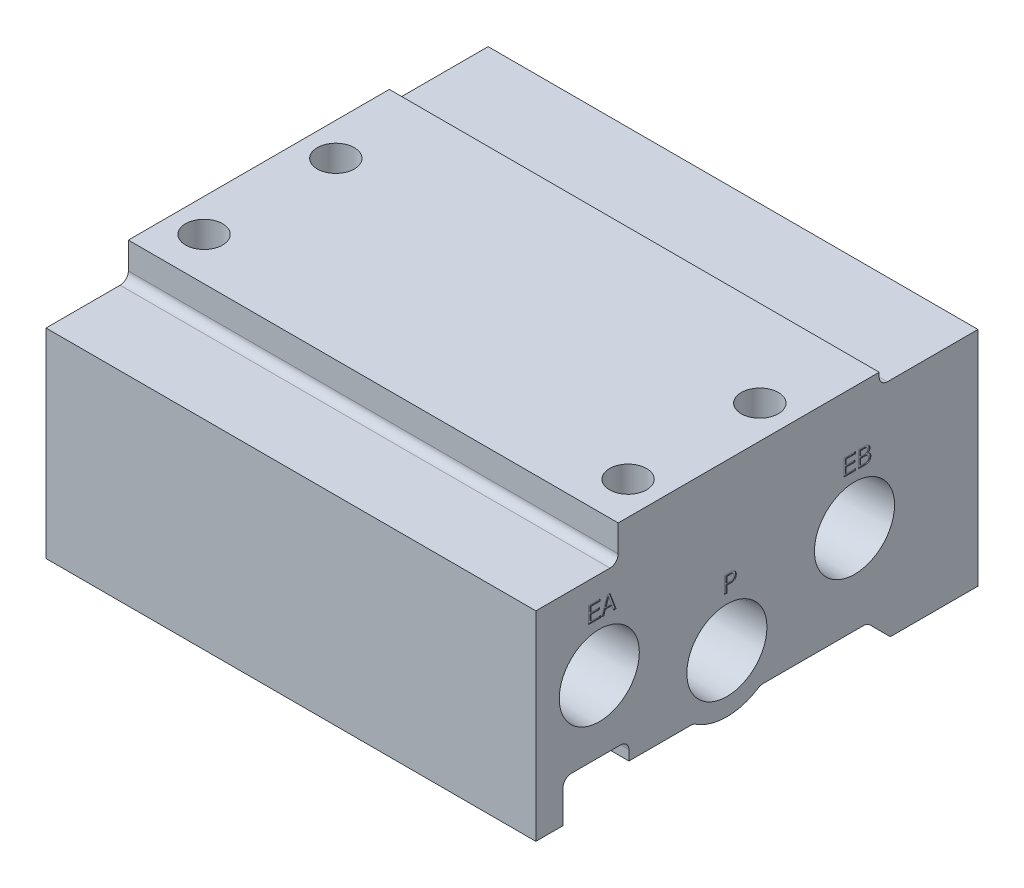
SolidWorks part; units mm, degrees
material "6061-T6 (SS)"
ref_plane "Front" through (0, 0, 0) normal (0, 0, 1) x (1, 0, 0)
ref_plane "Top" through (0, 0, 0) normal (0, 1, 0) x (1, 0, 0)
ref_plane "Right" through (0, 0, 0) normal (1, 0, 0) x (0, 0, -1)
sketch "Alum Ext Sketch" plane through (0, 0, 0) normal (1, 0, 0) x (0, 0, -1)
  line L1 (-26.85, 0) -> (26.85, 0)
  line L2 (-26.85, 0) -> (-26.85, -28.5)
  line L4 (26.85, 0) -> (26.85, -28.5)
  line L7 (0, 5.7104) -> (0, -31.2342) construction
  line L8 (-26.85, -28.5) -> (26.85, -28.5)
  dimension "Depth" = 53.7
  dimension "Height" = 28.5
extrude "Alum Ext" add sketch "Alum Ext Sketch" against normal up to surface (59.5 mm away)
sketch "Bottom_Profile 20 Sketch" [suppressed] plane through (0, 0, 0) normal (1, 0, 0) x (0, 0, -1)
  line L0 (-1, 0) -> (-1, -38.4475) construction
  line L1 (-21.54, -20) -> (-21.54, -13.45)
  line L2 (-24.5, -20) -> (24.5, -20) construction
  line L3 (-21.54, -13.45) -> (-21.1875, -13.45)
  line L4 (-13.8125, -13.45) -> (-4.6875, -13.45)
  line L5 (11.8125, -13.45) -> (2.6875, -13.45)
  line L6 (21.54, -13.45) -> (19.1875, -13.45)
  line L7 (21.54, -20) -> (21.54, -13.45)
  line L8 (24.5, -20) -> (24.5, 0) construction
  line L9 (-24.5, 0) -> (-24.5, -20) construction
  line L10 (24.5, 0) -> (-24.5, 0) construction
  line L11 (21.54, -16.725) -> (24.5, -16.725) construction
  line L12 (-21.54, -16.725) -> (-24.5, -16.725) construction
  line L13 (-24.5, -20) -> (-24.5, 0) construction
  line L14 (-21.54, -20) -> (21.54, -20)
  line L15 (-10.2716, -5) -> (-8.2284, -5)
  line L17 (-10.9481, -11.65) -> (-7.5519, -11.65)
  line L18 (-1, 9.9528) -> (-1, -11.3216) construction
  line L19 (8.9481, -11.65) -> (5.5519, -11.65)
  line L20 (8.2716, -5) -> (6.2284, -5)
  line L21 (24.5, 0) -> (-24.5, 0) construction
  arc A0 (-21.1875, -13.45) -> (-13.8125, -13.45) centre (-17.5, -7.5) ccw
  arc A1 (-4.6875, -13.45) -> (2.6875, -13.45) centre (-1, -7.5) ccw
  arc A2 (19.1875, -13.45) -> (11.8125, -13.45) centre (15.5, -7.5) cw
  arc A3 (-10.7535, -5.6333) -> (-11.3849, -10.9067) centre (-17.5, -7.5) cw
  arc A4 (-10.7535, -5.6333) -> (-10.2716, -5) centre (-10.2716, -5.5) cw
  arc A5 (-10.9481, -11.65) -> (-11.3849, -10.9067) centre (-10.9481, -11.15) cw
  arc A6 (-7.5519, -11.65) -> (-7.1151, -10.9067) centre (-7.5519, -11.15) ccw
  arc A7 (-7.7465, -5.6333) -> (-8.2284, -5) centre (-8.2284, -5.5) ccw
  arc A8 (-7.7465, -5.6333) -> (-7.1151, -10.9067) centre (-1, -7.5) ccw
  arc A9 (5.7465, -5.6333) -> (5.1151, -10.9067) centre (-1, -7.5) cw
  arc A10 (5.7465, -5.6333) -> (6.2284, -5) centre (6.2284, -5.5) cw
  arc A11 (5.5519, -11.65) -> (5.1151, -10.9067) centre (5.5519, -11.15) cw
  arc A12 (8.9481, -11.65) -> (9.3849, -10.9067) centre (8.9481, -11.15) ccw
  arc A13 (8.7535, -5.6333) -> (8.2716, -5) centre (8.2716, -5.5) ccw
  arc A14 (8.7535, -5.6333) -> (9.3849, -10.9067) centre (15.5, -7.5) ccw
  dimension "D1" = 23.5
  dimension "Wall_Radius" = 7
  dimension "D2" = 0.5
  dimension "D4" = 5
  dimension "D3" = 1.8
  dimension "Thickness" = 2.96
  dimension "Port_Loc_Z" = 16.5
  dimension "Port_Loc_Y" = 12.5
  dimension "Body_Thickness" = 13.45
extrude "Bottom_Profile 20" [suppressed] cut sketch "Bottom_Profile 20 Sketch" against normal through all
fillet "Ext_Fillets" [suppressed] radius 0.25
sketch "MGT_Holes Sketch" plane through (0, 0, 0) normal (0, 1, 0) x (1, 0, 0)
  line L1 (-29.75, 26.85) -> (-29.75, -50.1534) construction
  line L2 (-59.5, 26.85) -> (0, 26.85) construction
  line L3 (0, 0) -> (0, 12.4211) construction
  line L4 (-59.5, -26.85) -> (0, -26.85) construction
  line L6 (-59.5, -26.85) -> (-59.5, 26.85) construction
  circle A0 centre (-55.5, 4.35) radius 2.25
  circle A1 centre (-55.5, -11.65) radius 2.25
  circle A4 centre (-4, 4.35) radius 2.25
  circle A5 centre (-4, -11.65) radius 2.25
  dimension "Dia" = 4.5
  dimension "Loc_X" = 4
  dimension "Loc_Z" = 15.2
  dimension "C_2_C" = 16
extrude "MGT_Holes" cut sketch "MGT_Holes Sketch" against normal through all
sketch "Top_Profile_41 Sketch" plane through (0, 0, 0) normal (1, 0, 0) x (0, 0, -1)
  line L0 (-26.85, -4.25) -> (-16.85, -4.25)
  line L1 (-16.85, -4.25) -> (-16.85, 0)
  line L2 (26.85, 0) -> (-26.85, 0) construction
  line L3 (14.85, 0) -> (14.85, -1.5)
  line L4 (14.85, -1.5) -> (26.85, -1.5)
  line L5 (26.85, -28.5) -> (26.85, 0) construction
  line L6 (-26.85, -28.5) -> (26.85, -28.5) construction
  line L7 (-26.85, 0) -> (-26.85, -28.5) construction
  line L8 (26.85, -1.5) -> (26.85, 0)
  line L9 (-26.85, 0) -> (-26.85, -4.25)
  line L10 (26.85, 0) -> (14.85, 0)
  line L11 (-16.85, 0) -> (-26.85, 0)
  dimension "Back" = 12
  dimension "Back Height" = 27
  dimension "Front" = 10
  dimension "Front_Height" = 24.25
extrude "Top_Profile_41" cut sketch "Top_Profile_41 Sketch" against normal through all
sketch "Bottom_Profile_41 Sketch" plane through (0, 0, 0) normal (1, 0, 0) x (0, 0, -1)
  line L0 (16.2, -28.5) -> (13.4, -25.7)
  line L1 (-26.85, -28.5) -> (26.85, -28.5) construction
  line L2 (13.4, -25.7) -> (0.4132, -25.7)
  line L3 (-15.55, -25.7) -> (-15.55, -23.5)
  line L4 (-15.55, -23.5) -> (-23.55, -23.5)
  line L5 (-23.55, -23.5) -> (-23.55, -28.5)
  line L6 (26.85, -28.5) -> (-26.85, -28.5) construction
  line L7 (26.85, -28.5) -> (26.85, -1.5) construction
  line L8 (-26.85, -4.25) -> (-26.85, -28.5) construction
  line L9 (-26.85, -28.5) -> (-26.85, -4.25) construction
  line L10 (-7.7132, -25.7) -> (-15.55, -25.7)
  line L11 (-23.55, -28.5) -> (16.2, -28.5)
  arc A0 (-7.7132, -25.7) -> (0.4132, -25.7) centre (-3.65, -20) ccw
  dimension "D1" = 8.5
  dimension "D2" = 23.2
  dimension "Radius" = 7
  dimension "Back_Width" = 13.45
  dimension "Back_Depth" = 2.8
  dimension "Front_Width" = 3.3
  dimension "Front_Depth" = 5
  dimension "Groove" = 8
  dimension "Angle" = 45
extrude "Bottom_Profile_41" cut sketch "Bottom_Profile_41 Sketch" against normal through all
fillet "Rounds_41" radius 1 7 edges at (-29.75, -4.25, 16.85) (-29.75, -1.5, -14.85) (-29.75, -25.7, -0.4132) (-29.75, -23.5, 23.55) (-29.75, -23.5, 15.55) (-29.75, -25.7, 7.7132) (-29.75, -25.7, -13.4)
sketch "Profile_42 Sketch" [suppressed] plane through (0, 0, 0) normal (1, 0, 0) x (0, 0, -1)
  line L0 (-13.9, -32) -> (-12.9, -31)
  line L1 (-27.85, -32) -> (27.85, -32) construction
  line L2 (-12.9, -31) -> (12.9, -31)
  line L3 (12.9, -31) -> (13.9, -32)
  line L4 (13.9, -32) -> (-13.9, -32)
  line L5 (0, 0) -> (0, -41.5568) construction
  dimension "Width" = 25.8
  dimension "Angle" = 90
  dimension "Depth" = 1
extrude "Profile_42" [suppressed] cut sketch "Profile_42 Sketch" against normal through all
fillet "Fillets_42" [suppressed] radius 0.5
sketch "20 Port Designations Sketch" [suppressed] plane through (2.9671, 0, 3.015) normal (0, 1, 0) x (0, 0, 1)
  line L0 (21.485, -51.4671) -> (-27.515, -51.4671) construction
  line L2 (-27.515, -51.4671) -> (-27.515, -2.9671) construction
  line L3 (21.485, -51.4671) -> (21.485, -2.9671) construction
  text T0 "EA"
  text T1 "P" font "Swis721 BT" height 3.5
  text T2 "EB" font "Swis721 BT" height 3.5
  dimension "D1" = 3
  dimension "D2" = 4
  dimension "D3" = 23
  dimension "D4" = 11
extrude "20 Port Designations" [suppressed] cut sketch "20 Port Designations Sketch" against normal blind 0.1
sketch "20 Port Designations2 Sketch" [suppressed] plane through (-31.3648, 0, 0.1552) normal (0, 1, 0) x (0, 0, -1)
  line L0 (24.6552, -31.3648) -> (-24.3448, -31.3648) construction
  line L1 (24.6552, 17.1352) -> (24.6552, -31.3648) construction
  line L2 (-24.3448, 17.1352) -> (-24.3448, -31.3648) construction
  text T0 "EB"
  text T1 "P"
  text T2 "EA"
  dimension "D1" = 3
  dimension "D2" = 26.5
  dimension "D3" = 4
  dimension "D4" = 11
extrude "20 Port Designations2" [suppressed] cut sketch "20 Port Designations2 Sketch" against normal blind 0.1
hole_wizard "Ports" positions "Ports Loc Sketch" profile "Ports Profile Sketch" size "1/8" standard "ISO"
sketch "Ports Loc Sketch" plane through (0, 0, 0) normal (1, 0, 0) x (0, 0, -1)
  line L1 (-3.65, -20) -> (-3.65, -0.9405) construction
  line L5 (-26.85, -28.5) -> (-23.55, -28.5) construction
  line L7 (-26.85, -4.25) -> (-26.85, -28.5) construction
  point P0 (-3.65, -20)
  point P1 (11.85, -14.9)
  point P3 (-19.15, -14.9)
  dimension "Loc_Z" = 23.2
  dimension "C_2_C-Z" = 15.5
  dimension "C_2_C-Y" = 8.5
  dimension "Loc_Y" = 13.6
sketch "Ports Profile Sketch" plane through (0, -20, 3.65) normal (0, 1, 0) x (0, 0, -1)
  line L0 (0, 0) -> (0, 22.45)
  line L1 (3.95, 18.5) -> (0, 22.45)
  line L2 (-3.95, 18.5) -> (0, 22.45) construction
  line L3 (3.95, 18.5) -> (3.95, 7.4)
  line L4 (3.95, 7.4) -> (4.633, 7.4)
  line L5 (4.633, 7.4) -> (4.864, 0)
  line L6 (-4.633, 7.4) -> (-4.864, 0) construction
  line L7 (4.864, 0) -> (0, 0)
  line L8 (0, -6.35) -> (0, 107.95) construction
  line L11 (-3.95, 7.4) -> (-4.633, 7.4) construction
  dimension "Tap Drill Dia." = 7.9
  dimension "Tap Drill Depth" = 18.5
  dimension "Thread Dia." = 9.728
  dimension "Thread Angle" = 3.576
  dimension "Thread Depth" = 7.4
  dimension "Drill Angle" = 90
hole_wizard "Ports Mirror" positions "Ports Mirror Loc Sketch" profile "Ports Mirror Profile Sketch" size "1/8" standard "ISO"
sketch "Ports Mirror Loc Sketch" plane through (-59.5, 0, 0) normal (-1, 0, 0) x (0, 0, 1)
  point P0 (-11.85, -14.9)
  point P1 (3.65, -20)
  point P4 (19.15, -14.9)
sketch "Ports Mirror Profile Sketch" plane through (-59.5, -14.9, -11.85) normal (0, 1, 0) x (0, 0, 1)
  line L0 (0, 0) -> (0, 15.885)
  line L1 (3.95, 11.935) -> (0, 15.885)
  line L2 (-3.95, 11.935) -> (0, 15.885) construction
  line L3 (3.95, 11.935) -> (3.95, 7.4)
  line L4 (3.95, 7.4) -> (4.633, 7.4)
  line L5 (4.633, 7.4) -> (4.864, 0)
  line L6 (-4.633, 7.4) -> (-4.864, 0) construction
  line L7 (4.864, 0) -> (0, 0)
  line L8 (0, -6.35) -> (0, 107.95) construction
  line L11 (-3.95, 7.4) -> (-4.633, 7.4) construction
  dimension "Tap Drill Dia." = 7.9
  dimension "Tap Drill Depth" = 11.935
  dimension "Thread Dia." = 9.728
  dimension "Thread Angle" = 3.576
  dimension "Thread Depth" = 7.4
  dimension "Drill Angle" = 90
hole_wizard "Pilot Ports" [suppressed] positions "Pilot Ports Loc Sketch" profile "Pilot Ports Profile Sketch" tap size "M5x0.8" standard "JIS"
sketch "Pilot Ports Loc Sketch" [suppressed] plane through (0, 0, 0) normal (1, 0, 0) x (0, 0, -1)
  line L1 (14.1071, -32) -> (27.85, -32) construction
  circle A0 centre (-4.65, -24) radius 4.864 construction
  point P0 (14.75, -4)
  point P1 (-19.35, -4)
  dimension "D2" = 19.4
  dimension "D3" = 14.7
  dimension "D1" = 28
sketch "Pilot Ports Profile Sketch" [suppressed] plane through (0, -4, -14.75) normal (0, 1, 0) x (0, 0, -1)
  line L0 (0, 0) -> (0, 13.6618)
  line L1 (0, 13.6618) -> (2.1, 12.4)
  line L2 (2.1, 12.4) -> (2.1, 10)
  line L3 (2.1, 10) -> (2.5, 10)
  line L4 (2.5, 10) -> (2.5, 0)
  line L5 (2.5, 0) -> (0, 0)
  line L10 (0, 13.6618) -> (-2.1, 12.4) construction
  line L11 (0, -6.35) -> (0, 107.95) construction
  dimension "Tap Drill Dia." = 4.2
  dimension "Tap Drill Depth" = 12.4
  dimension "Thread Major Dia." = 5
  dimension "Thread Depth" = 10
  dimension "Drill Angle" = 118
hole_wizard "Pilot Ports Mirror" [suppressed] positions "Pilot Ports Mirror Loc Sketch" profile "Pilot Ports Mirror Profile Sketch" tap size "M5" standard "ISO"
sketch "Pilot Ports Mirror Loc Sketch" [suppressed] plane through (-101.5, 0, 0) normal (-1, 0, 0) x (0, 0, 1)
  point P0 (19.35, -4)
  point P1 (-14.75, -4)
sketch "Pilot Ports Mirror Profile Sketch" [suppressed] plane through (-101.5, -4, 19.35) normal (0, 1, 0) x (0, 0, 1)
  line L0 (0, 0) -> (0, 13.6618)
  line L1 (0, 13.6618) -> (2.1, 12.4)
  line L2 (2.1, 12.4) -> (2.1, 10)
  line L3 (2.1, 10) -> (2.5, 10)
  line L4 (2.5, 10) -> (2.5, 0)
  line L5 (2.5, 0) -> (0, 0)
  line L10 (0, 13.6618) -> (-2.1, 12.4) construction
  line L11 (0, -6.35) -> (0, 107.95) construction
  dimension "Tap Drill Dia." = 4.2
  dimension "Tap Drill Depth" = 12.4
  dimension "Thread Major Dia." = 5
  dimension "Thread Depth" = 10
  dimension "Drill Angle" = 118
sketch "41,42 Port Labels1 Sketch" plane through (-59.5, 0, 0) normal (-1, 0, 0) x (0, 0, 1)
  text T0 "EB" font "Swis721 BT" height 2
  text T1 "P" font "Swis721 BT" height 2
  text T2 "EA" font "Swis721 BT" height 2
  dimension "D1" = 1.5
  dimension "D2" = 1.5
  dimension "D3" = 6
  dimension "D4" = 6
  dimension "D5" = 6
  dimension "D6" = 0.5
extrude "41,42 Port Labels1" cut sketch "41,42 Port Labels1 Sketch" against normal blind 0.1
sketch "41,42 Port Labels2 Sketch" plane through (0, 0, 0) normal (1, 0, 0) x (0, 0, -1)
  text T0 "EA" font "Swis721 BT" height 2
  text T1 "P" font "Swis721 BT" height 2
  text T2 "EB" font "Swis721 BT" height 2
  dimension "D1" = 6
  dimension "D2" = 6
  dimension "D3" = 0.5
  dimension "D4" = 6
  dimension "D5" = 1.5
  dimension "D6" = 1.5
extrude "41,42 Port Labels2" cut sketch "41,42 Port Labels2 Sketch" against normal blind 0.1
sketch "42 Pilot Labels1 Sketch" [suppressed] plane through (-101.5, 0, 0) normal (-1, 0, 0) x (0, 0, 1)
  text T0 "PE" font "Swis721 BT" height 2
  text T1 "X" font "Swis721 BT" height 2
extrude "42 Pilot Labels1" [suppressed] cut sketch "42 Pilot Labels1 Sketch" against normal blind 0.1
sketch "42 Pilot Labels2 Sketch" [suppressed] plane through (0, 0, 0) normal (1, 0, 0) x (0, 0, -1)
  text T0 "X" font "Swis721 BT" height 2
  text T1 "PE" font "Swis721 BT" height 2
extrude "42 Pilot Labels2" [suppressed] cut sketch "42 Pilot Labels2 Sketch" against normal blind 0.1
sketch "41,42 A,B Labels Sketch" plane through (0, 0, -26.85) normal (0, 0, 1) x (1, 0, 0)
  line L0 (-59.5, -28.5) -> (0, -28.5) construction
  line L1 (-59.5, -1.5) -> (-59.5, -28.5) construction
  line L2 (0, -28.5) -> (0, -1.5) construction
  line L3 (-59.5, -28.5) -> (0, -28.5) construction
  text T0 "A"
  text T1 "B"
  text T2 "A"
  text T3 "B"
  point P12 (-59.5, -15)
  dimension "D1" = 5
  dimension "D2" = 11
  dimension "D3" = 1
  dimension "D4" = 18.5
  dimension "D5" = 8
  dimension "D6" = 4.5
extrude "41,42 A,B Labels" cut sketch "41,42 A,B Labels Sketch" along normal blind 0.1
